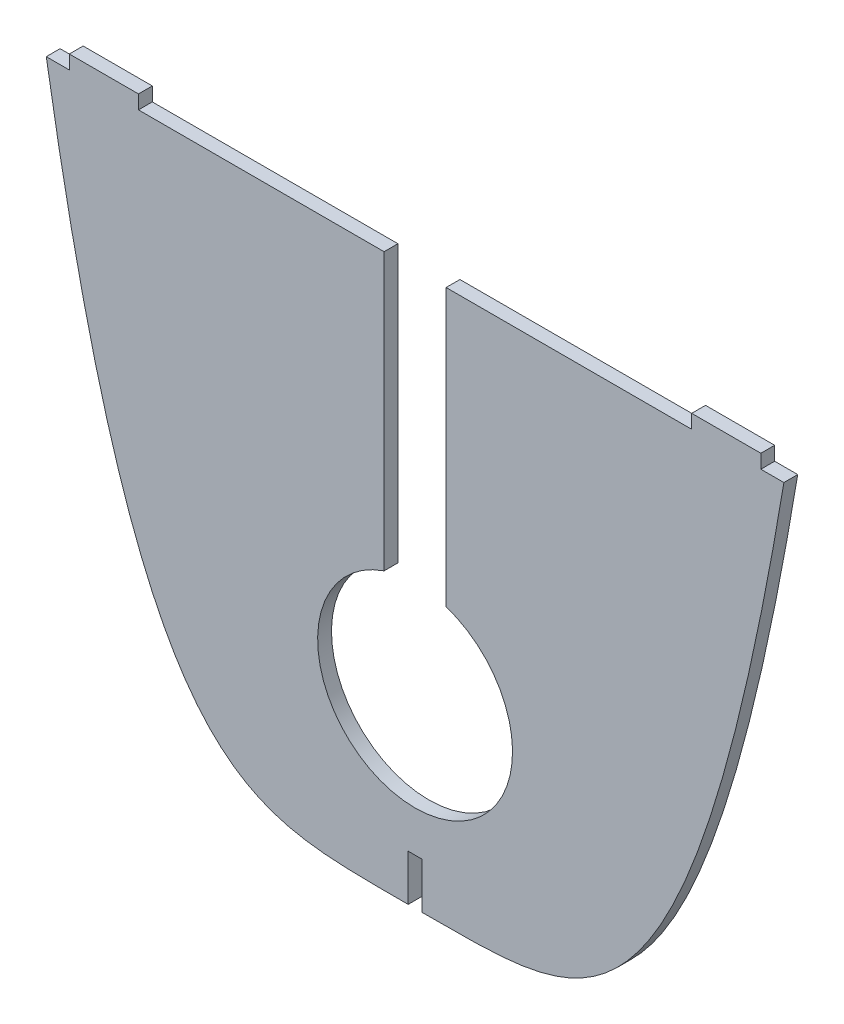
SolidWorks part; units mm, degrees
ref_plane "前视基准面" through (0, 0, 0) normal (0, 0, 1) x (1, 0, 0)
ref_plane "上视基准面" through (0, 0, 0) normal (0, 1, 0) x (1, 0, 0)
ref_plane "右视基准面" through (0, 0, 0) normal (1, 0, 0) x (0, 0, -1)
other "Configuration Table"
sketch "草图1" plane through (0, 0, 0) normal (0, 0, 1) x (1, 0, 0)
  line L2 (-80, 120) -> (-75, 120)
  line L5 (-75, 123) -> (-75, 120)
  line L6 (-60, 123) -> (-60, 120)
  line L7 (-55, 120) -> (-60, 120)
  line L8 (0, 0) -> (0, 135) construction
  line L9 (55, 120) -> (60, 120)
  line L10 (60, 120) -> (60, 123)
  line L11 (60, 123) -> (75, 123)
  line L12 (75, 123) -> (75, 120)
  line L13 (75, 120) -> (80, 120)
  line L14 (-75, 123) -> (-60, 123)
  arc A0 (-14.6979, 54.999) -> (14.6979, 54.999) centre (0, 40) ccw
  spline S0 degree 4 poles (-84.8994, 152.209) (-42.4497, -152.209) (0, 152.209) (42.4497, -152.209) (84.8994, 152.209) knots 0 0 0 0 0 1 1 1 1 1 construction
  spline S1 degree 4 poles (-80, 120) (-40, -120) (0, 120) (40, -120) (80, 120) knots 0.028854 0.028854 0.028854 0.028854 0.028854 0.971146 0.971146 0.971146 0.971146 0.971146
  spline S2 degree 2 poles (-55, 120) (-34.849, 68.7065) (-14.6979, 54.999) knots 0 0 0 0.366382 0.366382 0.366382
  spline S3 degree 2 poles (14.6979, 54.999) (34.849, 68.7065) (55, 120) knots 0.633618 0.633618 0.633618 1 1 1
extrude "凸台-拉伸1" add sketch "草图1" along normal blind 3 contours A0 S3 L9 L10 L11 L12 L13 S1 L2 L5 L14 L6 L7 S2
sketch "草图2" plane through (0, 0, 0) normal (0, 0, 1) x (1, 0, 0)
  line L0 (-55, 120) -> (55, 120)
  line L1 (-14.6979, 54.999) -> (14.6979, 54.999)
  parabola Q32 (-55, 120) -> (-14.6979, 54.999) focus (0, 60.8036) apex (0, 50) construction
  parabola Q33 (14.6979, 54.999) -> (55, 120) focus (0, 60.8036) apex (0, 50) construction
  parabola Q34 (-55, 120) -> (-14.6979, 54.999) focus (0, 60.8036) apex (0, 50)
  parabola Q35 (14.6979, 54.999) -> (55, 120) focus (0, 60.8036) apex (0, 50)
extrude "凸台-拉伸2" add sketch "草图2" along normal blind 3
sketch "草图3" plane through (0, 0, 0) normal (0, 0, 1) x (1, 0, 0)
  line L0 (-6.7251, 120) -> (6.7251, 120)
  line L1 (-60, 120) -> (60, 120) construction
  line L2 (-6.7251, 120) -> (-6.7251, 54.999)
  line L3 (-14.6979, 54.999) -> (14.6979, 54.999) construction
  line L4 (6.7251, 120) -> (6.7251, 54.999)
  line L5 (6.7251, 54.999) -> (-6.7251, 54.999)
  point P5 (0, 120)
extrude "切除-拉伸1" cut sketch "草图3" along normal blind 3
sketch "草图4" plane through (0, 0, 0) normal (0, 0, 1) x (1, 0, 0)
  circle A1 centre (0, 40) radius 21.1361
extrude "切除-拉伸2" cut sketch "草图4" along normal blind 3
sketch "草图5" plane through (0, 0, 3) normal (0, 0, 1) x (1, 0, 0)
  line L13 (-1.5, 10) -> (1.5, 10)
  line L14 (-1.5, 10) -> (-1.5, -5.9759)
  line L15 (-1.5, -5.9759) -> (1.5, -5.9759)
  line L16 (1.5, 10) -> (1.5, -5.9759)
  dimension "D1" = 1.5
  dimension "D2" = 3
  dimension "D3" = 10
extrude "切除-拉伸4" cut sketch "草图5" against normal blind 10
